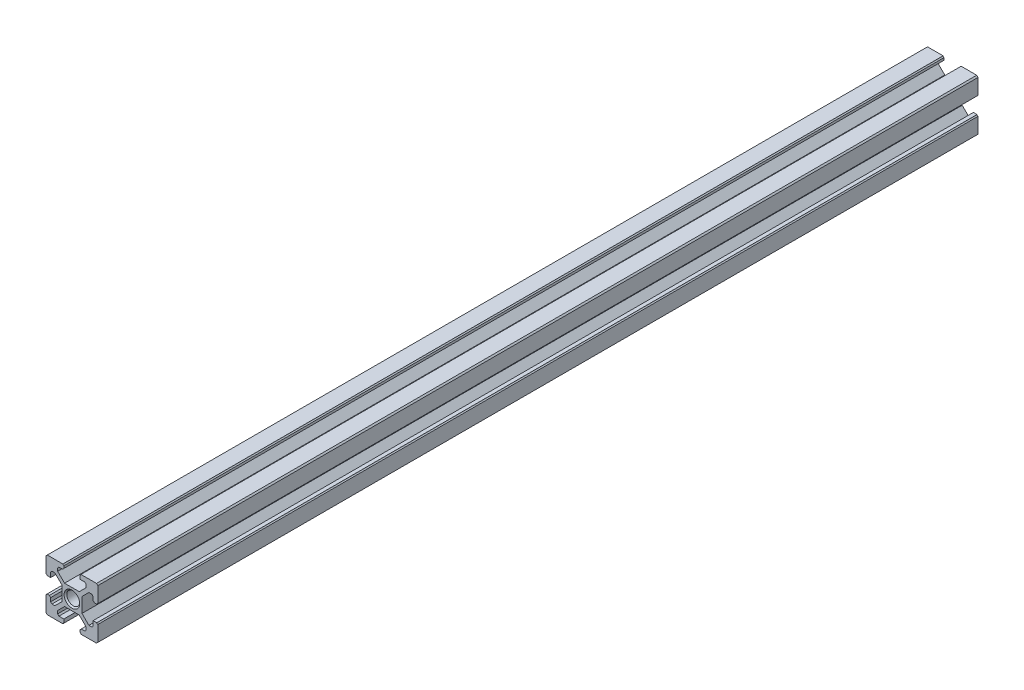
SolidWorks part; units mm, degrees
ref_plane "Front Plane" through (0, 0, 0) normal (0, 0, 1) x (1, 0, 0)
ref_plane "Top Plane" through (0, 0, 0) normal (0, 1, 0) x (1, 0, 0)
ref_plane "Right Plane" through (0, 0, 0) normal (1, 0, 0) x (0, 0, -1)
sketch "Sketch1" plane through (0, 0, 0) normal (0, 0, 1) x (1, 0, 0)
  line L0 (0, 10.7337) -> (0, 0.7337) construction
  line L1 (-9.5, 10) -> (-3.4865, 10)
  line L2 (-10, 9.5) -> (-10, 3.4865)
  line L3 (-9.5, -10) -> (-3.4865, -10)
  line L4 (10, 9.5) -> (10, 3.4865)
  line L5 (-9.75, 9.75) -> (9.75, -9.75) construction
  line L6 (-9.75, -9.75) -> (10, 10) construction
  line L7 (0, 0) -> (-10, 0) construction
  line L8 (3.1, 9.6135) -> (3.1, 8.2)
  line L9 (3.1, 8.2) -> (5, 8.2)
  line L10 (5.5, 7.7) -> (5.5, 6.5607)
  line L11 (5.5, 6.5607) -> (2.8393, 3.9)
  line L12 (2.8393, 3.9) -> (0, 3.9)
  line L13 (3.9, 2.8393) -> (3.9, 0)
  line L14 (6.5607, 5.5) -> (3.9, 2.8393)
  line L15 (9.6135, 3.1) -> (8.7, 3.1)
  line L16 (8.2, 3.6) -> (8.2, 5)
  line L17 (7.7, 5.5) -> (6.5607, 5.5)
  line L18 (3.4865, 10) -> (9.5, 10)
  line L19 (10, -3.4865) -> (10, -9.5)
  line L20 (5, 8.2) -> (5.5, 7.7)
  line L21 (8.2, 5) -> (7.7, 5.5)
  line L22 (9.5, 10) -> (10, 9.5)
  line L23 (8.7, 3.1) -> (8.2, 3.6)
  line L24 (3.9, -2.8393) -> (3.9, 0)
  line L25 (6.5607, -5.5) -> (3.9, -2.8393)
  line L26 (7.7, -5.5) -> (6.5607, -5.5)
  line L27 (8.2, -5) -> (7.7, -5.5)
  line L28 (8.2, -3.1) -> (8.2, -5)
  line L29 (9.6135, -3.1) -> (8.2, -3.1)
  line L30 (10, -3.4865) -> (10, -9.5)
  line L31 (10, -9.5) -> (9.5, -10)
  line L32 (9.5, -10) -> (3.4865, -10)
  line L33 (3.1, -9.6135) -> (3.1, -8.7)
  line L34 (3.1, -8.7) -> (3.6, -8.2)
  line L35 (3.6, -8.2) -> (5, -8.2)
  line L36 (5, -8.2) -> (5.5, -7.7)
  line L37 (5.5, -7.7) -> (5.5, -6.5607)
  line L38 (5.5, -6.5607) -> (2.8393, -3.9)
  line L39 (2.8393, -3.9) -> (0, -3.9)
  line L40 (-2.8393, -3.9) -> (0, -3.9)
  line L41 (-5.5, -6.5607) -> (-2.8393, -3.9)
  line L42 (-5.5, -7.7) -> (-5.5, -6.5607)
  line L43 (-5, -8.2) -> (-5.5, -7.7)
  line L44 (-3.1, -8.2) -> (-5, -8.2)
  line L45 (-3.1, -9.6135) -> (-3.1, -8.2)
  line L46 (-3.4865, -10) -> (-9.5, -10)
  line L47 (-9.5, -10) -> (-10, -9.5)
  line L48 (-10, -9.5) -> (-10, -3.4865)
  line L49 (-9.6135, -3.1) -> (-8.7, -3.1)
  line L50 (-8.7, -3.1) -> (-8.2, -3.6)
  line L51 (-8.2, -3.6) -> (-8.2, -5)
  line L52 (-8.2, -5) -> (-7.7, -5.5)
  line L53 (-7.7, -5.5) -> (-6.5607, -5.5)
  line L54 (-6.5607, -5.5) -> (-3.9, -2.8393)
  line L55 (-3.9, -2.8393) -> (-3.9, 0)
  line L56 (-3.9, 2.8393) -> (-3.9, 0)
  line L57 (-6.5607, 5.5) -> (-3.9, 2.8393)
  line L58 (-7.7, 5.5) -> (-6.5607, 5.5)
  line L59 (-8.2, 5) -> (-7.7, 5.5)
  line L60 (-8.2, 3.1) -> (-8.2, 5)
  line L61 (-9.6135, 3.1) -> (-8.2, 3.1)
  line L62 (-10, 3.4865) -> (-10, 9.5)
  line L63 (-10, 9.5) -> (-9.5, 10)
  line L64 (-9.5, 10) -> (-3.4865, 10)
  line L65 (-3.1, 9.6135) -> (-3.1, 8.7)
  line L66 (-3.1, 8.7) -> (-3.6, 8.2)
  line L67 (-3.6, 8.2) -> (-5, 8.2)
  line L68 (-5, 8.2) -> (-5.5, 7.7)
  line L69 (-5.5, 7.7) -> (-5.5, 6.5607)
  line L70 (-5.5, 6.5607) -> (-2.8393, 3.9)
  line L71 (-2.8393, 3.9) -> (0, 3.9)
  line L72 (3.4865, -10) -> (9.5, -10)
  line L73 (-10, -3.4865) -> (-10, -9.5)
  arc A0 (3.1, 9.6135) -> (3.4865, 10) centre (3.1, 10) ccw
  arc A1 (9.6135, 3.1) -> (10, 3.4865) centre (10, 3.1) cw
  arc A2 (9.6135, -3.1) -> (10, -3.4865) centre (10, -3.1) ccw
  arc A3 (3.1, -9.6135) -> (3.4865, -10) centre (3.1, -10) cw
  arc A4 (-3.1, -9.6135) -> (-3.4865, -10) centre (-3.1, -10) ccw
  arc A5 (-9.6135, -3.1) -> (-10, -3.4865) centre (-10, -3.1) cw
  arc A6 (-9.6135, 3.1) -> (-10, 3.4865) centre (-10, 3.1) ccw
  arc A7 (-3.1, 9.6135) -> (-3.4865, 10) centre (-3.1, 10) cw
  point P0 (0, 0)
  point P13 (5.5, 8.2)
  point P17 (3.1, 8.9068)
  point P22 (8.2, 3.1)
  point P23 (8.2, 5.5)
  point P103 (0, 0)
  dimension "D3" = 1.8
  dimension "D4" = 6.1
  dimension "D5" = 11
  dimension "D6" = 6.2
  dimension "D7" = 1.5
extrude "Boss-Extrude1" add sketch "Sketch1" along normal blind 340 contours L65 A7 L1 L63 L2 A6 L61 L60 L59 L58 L57 L56 L55 L54 L53 L52 L51 L50 L49 A5 L48 L47 L3 A4 L45 L44 L43 L42 L41 L40 L39 L38 L37 L36 L35 L34 L33 A3 L32 L31 L19 A2 L29 L28 L27 L26 L25 L24 L13 L14 L17
hole_wizard "M6x1.0 Tapped Hole1" positions "3DSketch1" profile "Sketch2" tap size "M6x1.0" standard "ANSI Metric"
sketch3d "3DSketch1"
  line L0 (3.9, -2.8393, 340) -> (3.9, 2.8393, 340) construction
  line L1 (2.8393, 3.9, 340) -> (-2.8393, 3.9, 340) construction
  point P0 (0, 0, 0)
  point P3 (0, 0, 0)
  point P5 (0, 0, 0)
  point P7 (0.9996, -8.1302, 0)
  point P9 (0, 0, 0)
  point P11 (0, 0, 340)
  dimension "D1" = 3.9
  dimension "D2" = 3.9
sketch "Sketch2" plane through (0, 0, 340) normal (1, 0, 0) x (0, -1, 0)
  line L0 (0, 0) -> (0, 30)
  line L1 (0, 30) -> (2.5, 28.4978)
  line L2 (2.5, 28.4978) -> (2.5, 0.525)
  line L3 (2.5, 0.525) -> (3.025, 0)
  line L5 (3.025, 0) -> (0, 0)
  line L6 (-2.5, 0.525) -> (-3.025, 0) construction
  line L10 (0, 30) -> (-2.5, 28.4978) construction
  line L11 (0, -6.35) -> (0, 107.95) construction
  dimension "Tap Drill Dia." = 5
  dimension "Tap Drill Depth" = 30
  dimension "Near C'Sink Dia." = 6.05
  dimension "Near C'Sink Angle" = 90
  dimension "Drill Angle" = 118
cosmetic thread "Hole Thread6" parameters "D1"=12, "D2"=6
hole_wizard "M6x1.0 Tapped Hole2" positions "3DSketch2" profile "Sketch3" tap size "M6x1.0" standard "ANSI Metric"
sketch3d "3DSketch2"
  line L0 (2.8393, 3.9, 0) -> (-2.8393, 3.9, 0) construction
  line L1 (3.9, -2.8393, 0) -> (3.9, 2.8393, 0) construction
  point P3 (0, 0, 0)
  dimension "D1" = 3.9
  dimension "D2" = 3.9
sketch "Sketch3" plane through (0, 0, 0) normal (1, 0, 0) x (0, 1, 0)
  line L0 (0, 0) -> (0, 30)
  line L1 (0, 30) -> (2.5, 28.4978)
  line L2 (2.5, 28.4978) -> (2.5, 0.525)
  line L3 (2.5, 0.525) -> (3.025, 0)
  line L5 (3.025, 0) -> (0, 0)
  line L6 (-2.5, 0.525) -> (-3.025, 0) construction
  line L10 (0, 30) -> (-2.5, 28.4978) construction
  line L11 (0, -6.35) -> (0, 107.95) construction
  dimension "Tap Drill Dia." = 5
  dimension "Tap Drill Depth" = 30
  dimension "Near C'Sink Dia." = 6.05
  dimension "Near C'Sink Angle" = 90
  dimension "Drill Angle" = 118
cosmetic thread "Hole Thread7" parameters "D1"=12, "D2"=6
